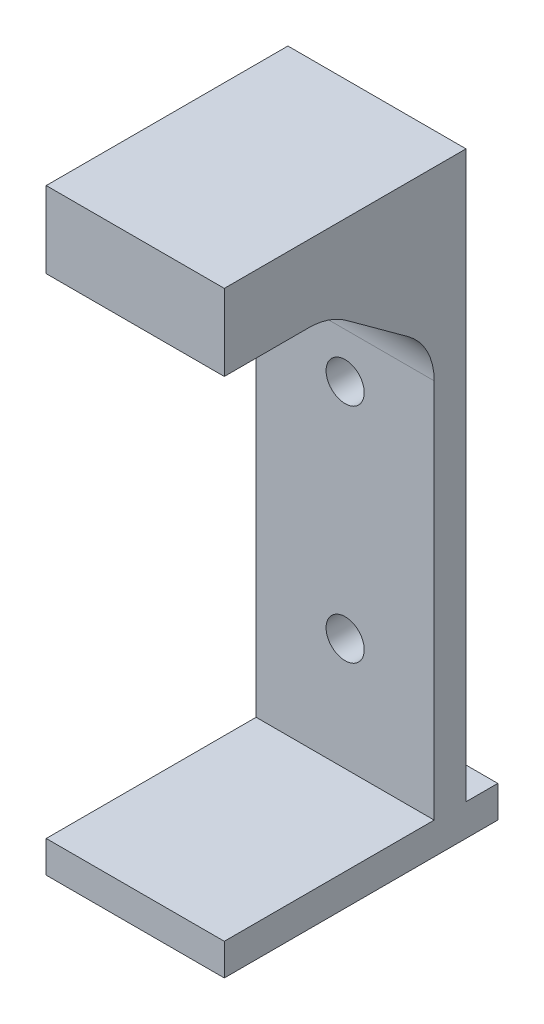
SolidWorks part; units mm, degrees
ref_plane "Front Plane" through (0, 0, 0) normal (0, 0, 1) x (1, 0, 0)
ref_plane "Top Plane" through (0, 0, 0) normal (0, 1, 0) x (1, 0, 0)
ref_plane "Right Plane" through (0, 0, 0) normal (1, 0, 0) x (0, 0, -1)
sketch "Sketch1" plane through (0, 0, 0) normal (0, 0, 1) x (1, 0, 0)
  line L0 (7, 26.35) -> (7, 8.85) construction
  line L1 (0, 0) -> (14, 0)
  line L2 (0, 0) -> (0, 28.85)
  line L3 (0, 28.85) -> (14, 28.85)
  line L4 (14, 0) -> (14, 28.85)
  circle A0 centre (7, 26.35) radius 1.5
  circle A1 centre (7, 8.85) radius 1.5
  dimension "D3" = 3
  dimension "D1" = 28.85
  dimension "D2" = 17.5
  dimension "D4" = 2.5
  dimension "D5" = 14
  dimension "D6" = 7
extrude "Boss-Extrude1" add sketch "Sketch1" along normal blind 2.5
sketch "Sketch3" plane through (0, 0, 2.5) normal (0, 0, 1) x (1, 0, 0)
  line L1 (0, 0) -> (14, 0)
  line L2 (0, 0) -> (0, -2)
  line L3 (0, -2) -> (14, -2)
  line L4 (14, 0) -> (14, -2)
  dimension "D1" = 2
  dimension "D2" = 14
extrude "Boss-Extrude2" add sketch "Sketch3" along normal blind 16.5 and the other way blind 5
sketch "Sketch4" plane through (0, 28.85, 0) normal (0, 1, 0) x (1, 0, 0)
  line L1 (0, 0) -> (14, 0)
  line L2 (0, 0) -> (0, -2.5)
  line L3 (0, -2.5) -> (14, -2.5)
  line L4 (14, 0) -> (14, -2.5)
extrude "Boss-Extrude3" add sketch "Sketch4" along normal blind 15.6
sketch "Sketch5" plane through (0, 0, 19) normal (0, 0, 1) x (1, 0, 0)
  line L1 (0, 0) -> (14, 0)
  line L2 (0, 0) -> (0, -2.5)
  line L3 (0, -2.5) -> (14, -2.5)
  line L4 (14, 0) -> (14, -2.5)
  dimension "D1" = 2.5
  dimension "D2" = 14
extrude "Boss-Extrude4" add sketch "Sketch5" against normal up to surface (21.5 mm away) up to face at (7, -1, -2.5)
sketch "Sketch6" plane through (0, 0, 2.5) normal (0, 0, 1) x (1, 0, 0)
  line L0 (14, 0) -> (14, 44.45) construction
  line L1 (0, 44.45) -> (14, 44.45)
  line L2 (0, 44.45) -> (0, 38.45)
  line L3 (0, 38.45) -> (14, 38.45)
  line L4 (14, 44.45) -> (14, 38.45)
  dimension "D1" = 6
extrude "Boss-Extrude5" add sketch "Sketch6" along normal up to surface (16.5 mm away)
sketch "Sketch7" plane through (14, 0, 0) normal (1, 0, 0) x (0, 0, -1)
  line L0 (-10.75, 38.45) -> (-2.5, 32.45)
  line L1 (-19, 38.45) -> (-2.5, 38.45) construction
  line L2 (-2.5, 0) -> (-2.5, 38.45) construction
  line L9 (-2.5, 0) -> (-19, 0)
  line L13 (-2.5, 38.45) -> (-2.5, 0)
  line L15 (-19, 0) -> (-19, -2.5)
  line L16 (-19, -2.5) -> (2.5, -2.5)
  line L17 (2.5, -2.5) -> (2.5, 0)
  line L18 (2.5, 0) -> (0, 0)
  line L19 (0, 0) -> (0, 44.45)
  line L20 (0, 44.45) -> (-19, 44.45)
  line L21 (-19, 44.45) -> (-19, 38.45)
  line L22 (-19, 38.45) -> (-2.5, 38.45)
  line L23 (-2.5, 38.45) -> (-2.5, 32.45)
  line L32 (-10.75, 38.45) -> (-2.5, 38.45)
  dimension "D1" = 6
  dimension "D2" = 0
extrude "Boss-Extrude6" add sketch "Sketch7" against normal up to surface (14 mm away) contours L32 L23 L0 up to face at (0, 16.08, 7.6)
fillet "Fillet2" radius 5 2 edges at (7, 38.45, 10.75) (7, 32.45, 2.5)
